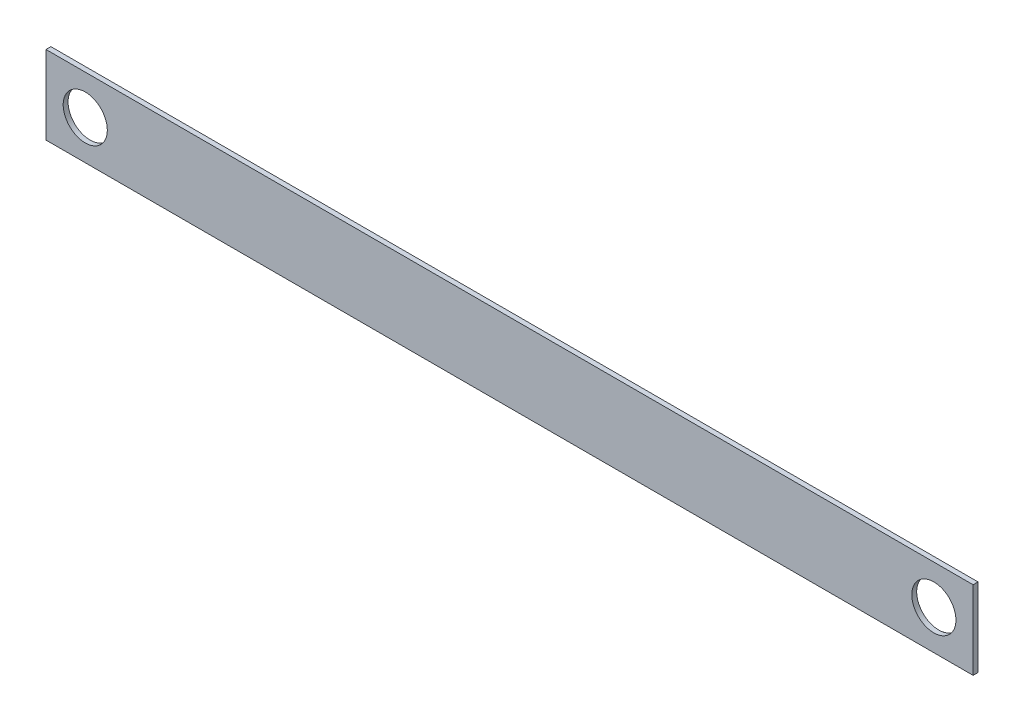
SolidWorks part; units mm, degrees
ref_plane "Front Plane" through (0, 0, 0) normal (0, 0, 1) x (1, 0, 0)
ref_plane "Top Plane" through (0, 0, 0) normal (0, 1, 0) x (1, 0, 0)
ref_plane "Right Plane" through (0, 0, 0) normal (1, 0, 0) x (0, 0, -1)
sketch "Sketch1" plane through (0, 0, 0) normal (0, 0, 1) x (1, 0, 0)
  line L1 (-300, -25.4) -> (300, -25.4)
  line L2 (-300, -25.4) -> (-300, 25.4)
  line L3 (-300, 25.4) -> (300, 25.4)
  line L4 (300, -25.4) -> (300, 25.4)
  line L5 (-300, -25.4) -> (300, 25.4) construction
  line L6 (-300, 25.4) -> (300, -25.4) construction
  circle A0 centre (-274.6, 0) radius 14.2875
  circle A1 centre (274.6, 0) radius 14.2875
  point P0 (0, 0)
  dimension "D5" = 28.575
  dimension "D6" = 28.575
  dimension "D1" = 600
  dimension "D2" = 50.8
  dimension "D3" = 25.4
  dimension "D4" = 25.4
  dimension "D7" = 25.4
  dimension "D8" = 25.4
extrude "Boss-Extrude1" add sketch "Sketch1" along normal blind 3.175
